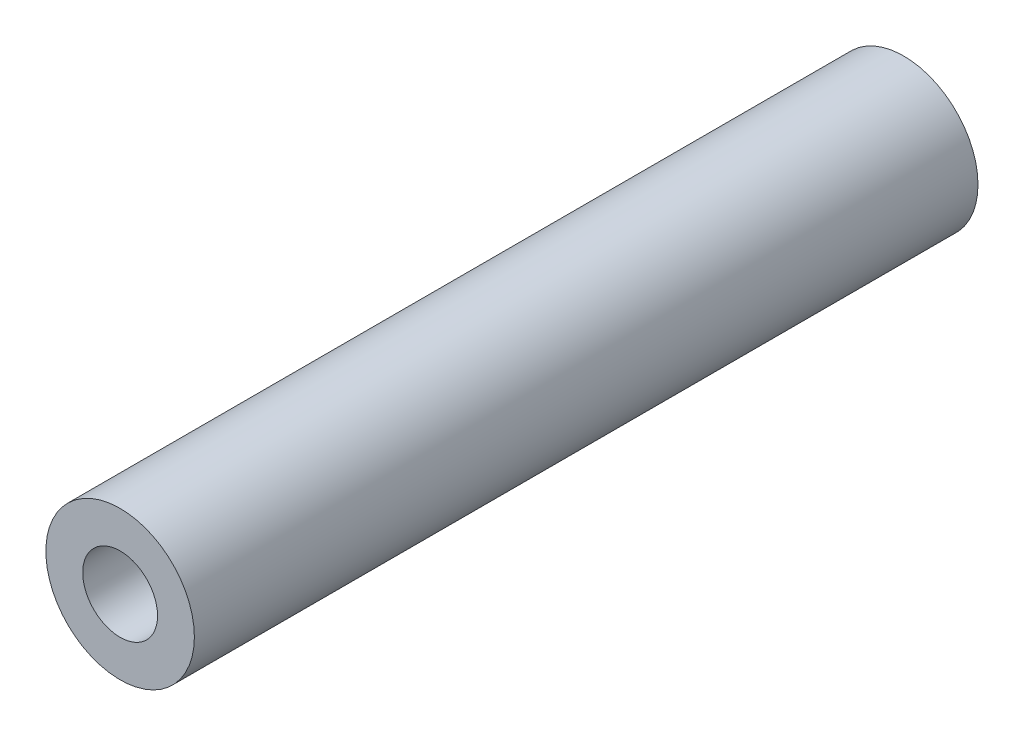
SolidWorks part; units mm, degrees
ref_plane "Front Plane" through (0, 0, 0) normal (0, 0, 1) x (1, 0, 0)
ref_plane "Top Plane" through (0, 0, 0) normal (0, 1, 0) x (1, 0, 0)
ref_plane "Right Plane" through (0, 0, 0) normal (1, 0, 0) x (0, 0, -1)
sketch "Sketch1" plane through (0, 0, 0) normal (0, 0, 1) x (1, 0, 0)
  circle A0 centre (0, 0) radius 6.35
  circle A1 centre (0, 0) radius 3.2004
  dimension "OD" = 12.7
  dimension "ID" = 6.4008
extrude "Extrude1" add sketch "Sketch1" along normal mid plane 67.0052
sketch "Sketch2" plane through (0, 0, 0) normal (1, 0, 0) x (0, 0, -1)
  line L0 (-33.5026, -3.2004) -> (33.5026, -3.2004) construction
  line L3 (33.5026, 3.2004) -> (-33.5026, 3.2004) construction
  line L5 (-33.5026, -3.2004) -> (33.5026, -3.2004)
  line L6 (33.5026, 3.2004) -> (-33.5026, 3.2004)
sketch "Sketch4" plane through (0, 0, 33.5026) normal (0, 0, 1) x (1, 0, 0)
  line L0 (0, 0) -> (-2.263, 2.263)
  line L1 (0, -55) -> (0, 55) construction
  circle A0 centre (0, 0) radius 3.2004 construction
  dimension "D1" = 45
